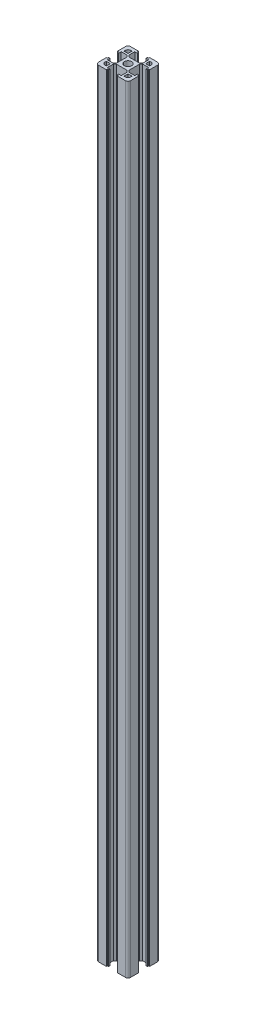
SolidWorks part; units mm, degrees
material "氧化铝"
ref_plane "前视基准面" through (0, 0, 0) normal (0, 0, 1) x (1, 0, 0)
ref_plane "上视基准面" through (0, 0, 0) normal (0, 1, 0) x (1, 0, 0)
ref_plane "右视基准面" through (0, 0, 0) normal (1, 0, 0) x (0, 0, -1)
sketch "草图1" plane through (0, 0, 0) normal (0, 1, 0) x (1, 0, 0)
  line L0 (-1000, 0) -> (49000, 0) construction
  line L1 (0, -1000) -> (0, 49000) construction
  line L2 (-12.8, 4.1) -> (-12.8, 6.4956)
  line L3 (-12.8, 6.4956) -> (-7.2734, 6.4956)
  line L4 (-7.2734, 6.4956) -> (-5.8, 5.0222)
  line L5 (-5.8, 5.0222) -> (-5.8, 0)
  line L6 (-12.8, 4.1) -> (-14, 4.1)
  line L7 (-14, 4.1) -> (-14, 5.2)
  line L8 (-14, 5.2) -> (-15, 5.2)
  line L9 (-15, 5.2) -> (-15, 12.5)
  line L10 (-12, 9.5) -> (-12, 8.25)
  line L11 (-12, 8.25) -> (-8.25, 8.25)
  line L12 (707.1068, -707.1068) -> (-34648.2323, 34648.2323) construction
  line L13 (-8.25, 12) -> (-8.25, 8.25)
  line L14 (-9.5, 12) -> (-8.25, 12)
  line L15 (-5.2, 15) -> (-12.5, 15)
  line L16 (-5.2, 14) -> (-5.2, 15)
  line L17 (-4.1, 14) -> (-5.2, 14)
  line L18 (-4.1, 12.8) -> (-4.1, 14)
  line L19 (-5.0222, 5.8) -> (0, 5.8)
  line L20 (-6.4956, 7.2734) -> (-5.0222, 5.8)
  line L21 (-6.4956, 12.8) -> (-6.4956, 7.2734)
  line L22 (-4.1, 12.8) -> (-6.4956, 12.8)
  line L23 (4.1, 12.8) -> (6.4956, 12.8)
  line L24 (6.4956, 12.8) -> (6.4956, 7.2734)
  line L25 (6.4956, 7.2734) -> (5.0222, 5.8)
  line L26 (5.0222, 5.8) -> (0, 5.8)
  line L27 (4.1, 12.8) -> (4.1, 14)
  line L28 (4.1, 14) -> (5.2, 14)
  line L29 (5.2, 14) -> (5.2, 15)
  line L30 (5.2, 15) -> (12.5, 15)
  line L31 (9.5, 12) -> (8.25, 12)
  line L32 (8.25, 12) -> (8.25, 8.25)
  line L33 (12, 8.25) -> (8.25, 8.25)
  line L34 (12, 9.5) -> (12, 8.25)
  line L35 (15, 5.2) -> (15, 12.5)
  line L36 (14, 5.2) -> (15, 5.2)
  line L37 (14, 4.1) -> (14, 5.2)
  line L38 (12.8, 4.1) -> (14, 4.1)
  line L39 (5.8, 5.0222) -> (5.8, 0)
  line L40 (7.2734, 6.4956) -> (5.8, 5.0222)
  line L41 (12.8, 6.4956) -> (7.2734, 6.4956)
  line L42 (12.8, 4.1) -> (12.8, 6.4956)
  line L43 (12.8, -4.1) -> (12.8, -6.4956)
  line L44 (12.8, -6.4956) -> (7.2734, -6.4956)
  line L45 (7.2734, -6.4956) -> (5.8, -5.0222)
  line L46 (5.8, -5.0222) -> (5.8, 0)
  line L47 (12.8, -4.1) -> (14, -4.1)
  line L48 (14, -4.1) -> (14, -5.2)
  line L49 (14, -5.2) -> (15, -5.2)
  line L50 (15, -5.2) -> (15, -12.5)
  line L51 (12, -9.5) -> (12, -8.25)
  line L52 (12, -8.25) -> (8.25, -8.25)
  line L53 (8.25, -12) -> (8.25, -8.25)
  line L54 (9.5, -12) -> (8.25, -12)
  line L55 (5.2, -15) -> (12.5, -15)
  line L56 (5.2, -14) -> (5.2, -15)
  line L57 (4.1, -14) -> (5.2, -14)
  line L58 (4.1, -12.8) -> (4.1, -14)
  line L59 (5.0222, -5.8) -> (0, -5.8)
  line L60 (6.4956, -7.2734) -> (5.0222, -5.8)
  line L61 (6.4956, -12.8) -> (6.4956, -7.2734)
  line L62 (4.1, -12.8) -> (6.4956, -12.8)
  line L63 (-4.1, -12.8) -> (-6.4956, -12.8)
  line L64 (-6.4956, -12.8) -> (-6.4956, -7.2734)
  line L65 (-6.4956, -7.2734) -> (-5.0222, -5.8)
  line L66 (-5.0222, -5.8) -> (0, -5.8)
  line L67 (-4.1, -12.8) -> (-4.1, -14)
  line L68 (-4.1, -14) -> (-5.2, -14)
  line L69 (-5.2, -14) -> (-5.2, -15)
  line L70 (-5.2, -15) -> (-12.5, -15)
  line L71 (-9.5, -12) -> (-8.25, -12)
  line L72 (-8.25, -12) -> (-8.25, -8.25)
  line L73 (-12, -8.25) -> (-8.25, -8.25)
  line L74 (-12, -9.5) -> (-12, -8.25)
  line L75 (-15, -5.2) -> (-15, -12.5)
  line L76 (-14, -5.2) -> (-15, -5.2)
  line L77 (-14, -4.1) -> (-14, -5.2)
  line L78 (-12.8, -4.1) -> (-14, -4.1)
  line L79 (-5.8, -5.0222) -> (-5.8, 0)
  line L80 (-7.2734, -6.4956) -> (-5.8, -5.0222)
  line L81 (-12.8, -6.4956) -> (-7.2734, -6.4956)
  line L82 (-12.8, -4.1) -> (-12.8, -6.4956)
  circle A0 centre (0, 0) radius 3.4
  arc A1 (-12, 9.5) -> (-9.5, 12) centre (-9.5, 9.5) cw
  arc A2 (-15, 12.5) -> (-12.5, 15) centre (-12.5, 12.5) cw
  arc A3 (9.5, 12) -> (12, 9.5) centre (9.5, 9.5) cw
  arc A4 (12.5, 15) -> (15, 12.5) centre (12.5, 12.5) cw
  arc A5 (12, -9.5) -> (9.5, -12) centre (9.5, -9.5) cw
  arc A6 (15, -12.5) -> (12.5, -15) centre (12.5, -12.5) cw
  arc A7 (-9.5, -12) -> (-12, -9.5) centre (-9.5, -9.5) cw
  arc A8 (-12.5, -15) -> (-15, -12.5) centre (-12.5, -12.5) cw
  point P32 (-12, 12)
  point P35 (-15, 15)
  point P114 (0, 0)
  dimension "D1" = 6.8
  dimension "D12" = 2.5
  dimension "D2" = 15
  dimension "D3" = 1.1
  dimension "D4" = 9.2
  dimension "D5" = 4.1
  dimension "D6" = 45
  dimension "D7" = 5.2
  dimension "D8" = 1
  dimension "D9" = 2.2
  dimension "D10" = 3.75
  dimension "D11" = 8.25
  dimension "D13" = 4
extrude "凸台-拉伸1" add sketch "草图1" along normal blind 725
